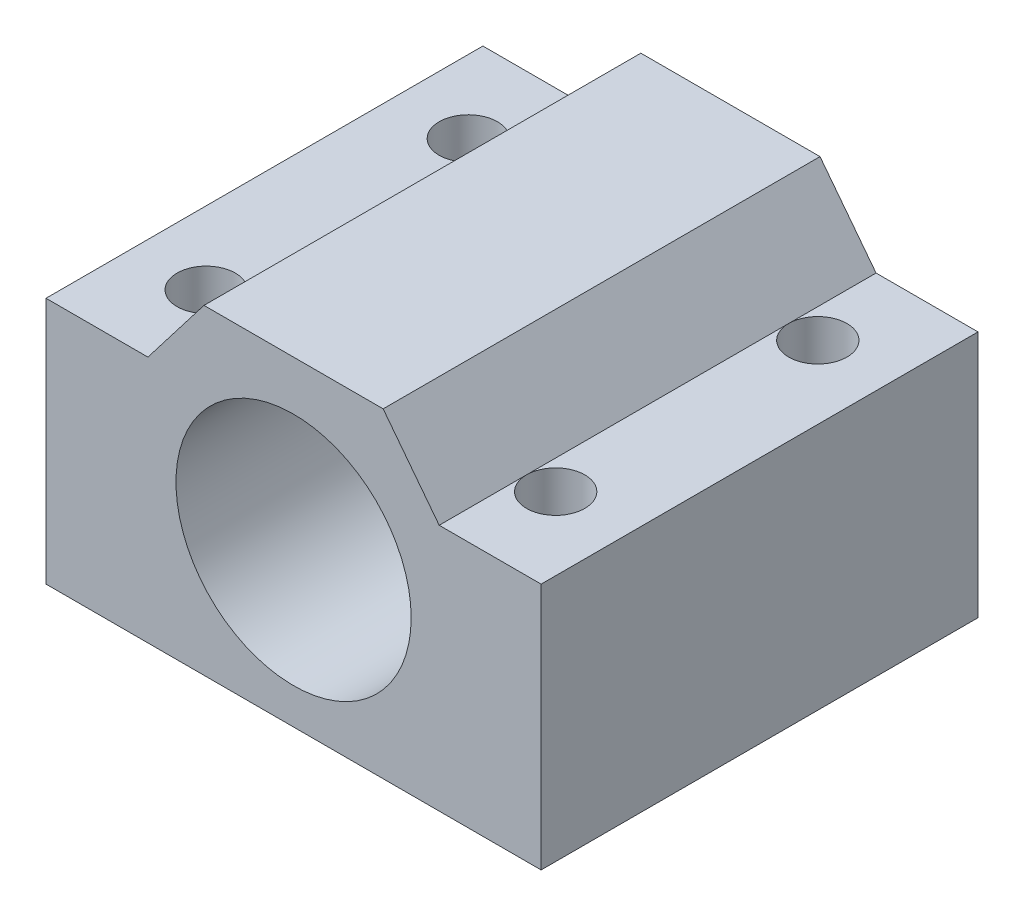
SolidWorks part; units mm, degrees
ref_plane "前视基准面" through (0, 0, 0) normal (0, 0, 1) x (1, 0, 0)
ref_plane "上视基准面" through (0, 0, 0) normal (0, 1, 0) x (1, 0, 0)
ref_plane "右视基准面" through (0, 0, 0) normal (1, 0, 0) x (0, 0, -1)
sketch "草图1" plane through (0, 0, 0) normal (0, 1, 0) x (1, 0, 0)
  line L0 (1.2257, 17.9561) -> (1.2257, -12.0439) construction
  line L1 (-15.7743, 17.9561) -> (18.2257, 17.9561)
  line L2 (-15.7743, 17.9561) -> (-15.7743, -12.0439)
  line L3 (-15.7743, -12.0439) -> (18.2257, -12.0439)
  line L4 (18.2257, 17.9561) -> (18.2257, -12.0439)
  line L5 (-15.7743, 2.9561) -> (18.2257, 2.9561) construction
  circle A0 centre (-10.7743, 11.9561) radius 2
  circle A1 centre (13.2257, 11.9561) radius 2
  circle A2 centre (13.2257, -6.0439) radius 2
  circle A3 centre (-10.7743, -6.0439) radius 2
  dimension "D3" = 24
  dimension "D5" = 4
  dimension "D1" = 34
  dimension "D2" = 30
  dimension "D4" = 18
extrude "凸台-拉伸1" add sketch "草图1" along normal blind 17
sketch "草图3" plane through (0, 0, 12.0439) normal (0, 0, 1) x (1, 0, 0)
  line L0 (1.2257, 17) -> (1.2257, -49983) construction
  line L1 (-15.7743, 17) -> (18.2257, 17) construction
  line L2 (-15.7743, 0) -> (18.2257, 0) construction
  line L3 (-8.7743, 17) -> (-4.9264, 22)
  line L4 (-4.9264, 22) -> (7.3778, 22)
  line L5 (11.2257, 17) -> (7.3778, 22)
  line L6 (-8.7743, 17) -> (11.2257, 17)
  line L7 (11.2257, 17) -> (11.2173, 16.9552)
  point P4 (1.2257, 17)
  point P7 (1.2257, 0)
  point P13 (1.2257, 22)
  line M7 (18.2257, 17) -> (-15.7743, 17)
  dimension "D1" = 5
  dimension "D2" = 20
extrude "凸台-拉伸3" add sketch "草图3" against normal up to surface (30 mm away) contours L0 L4 L3 L6 | L4 L0 L5 M7 up to face at (1.2257, 8.5, -17.9561)
sketch "草图4" plane through (0, 0, 12.0439) normal (0, 0, 1) x (1, 0, 0)
  line L0 (1.2257, 22) -> (1.2257, 0) construction
  line L1 (-4.9264, 22) -> (7.3778, 22) construction
  line L2 (-15.7743, 0) -> (18.2257, 0) construction
  circle A0 centre (1.2257, 10.5347) radius 8.0755
extrude "切除-拉伸1" cut sketch "草图4" against normal up to surface (30 mm away) up to face at (1.2257, 14, -17.9561)
